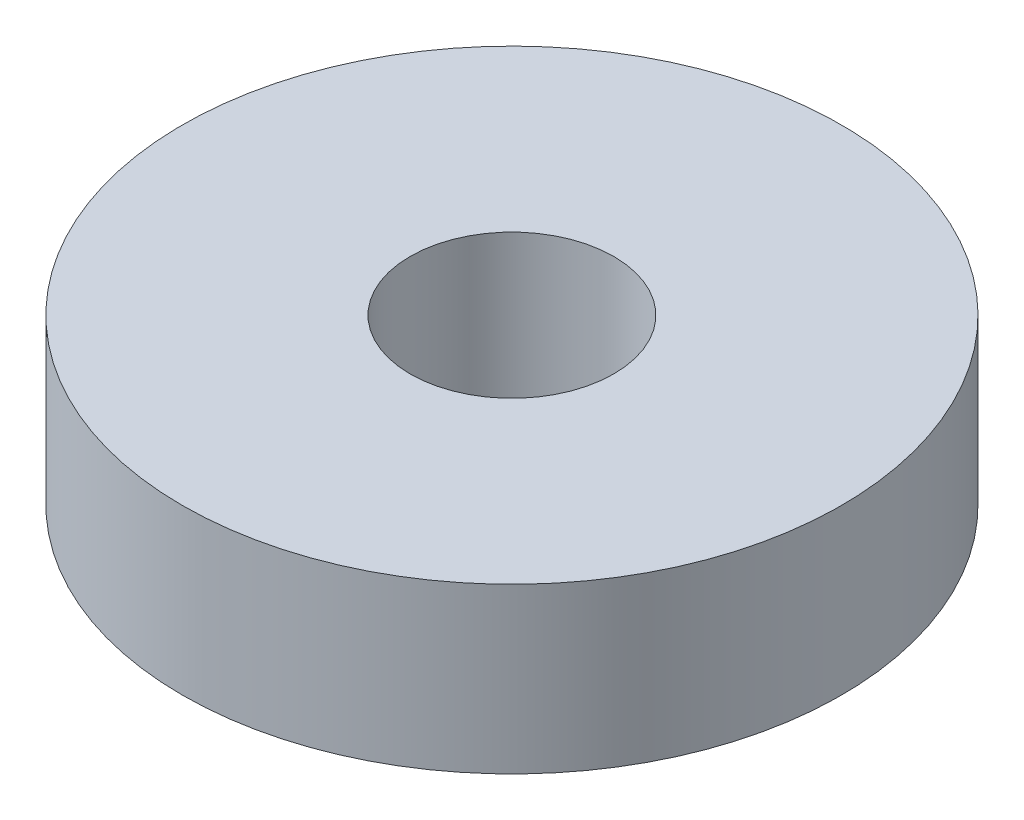
SolidWorks part; units mm, degrees
ref_plane "Front Plane" through (0, 0, 0) normal (0, 0, 1) x (1, 0, 0)
ref_plane "Top Plane" through (0, 0, 0) normal (0, 1, 0) x (1, 0, 0)
ref_plane "Right Plane" through (0, 0, 0) normal (1, 0, 0) x (0, 0, -1)
sketch "Sketch1" plane through (0, 0, 0) normal (0, 1, 0) x (1, 0, 0)
  circle A0 centre (0, 0) radius 20.6375
  circle A1 centre (0, 0) radius 6.3754
  dimension "D1" = 12.7508
  dimension "D2" = 41.275
extrude "Boss-Extrude1" add sketch "Sketch1" along normal blind 10.287
